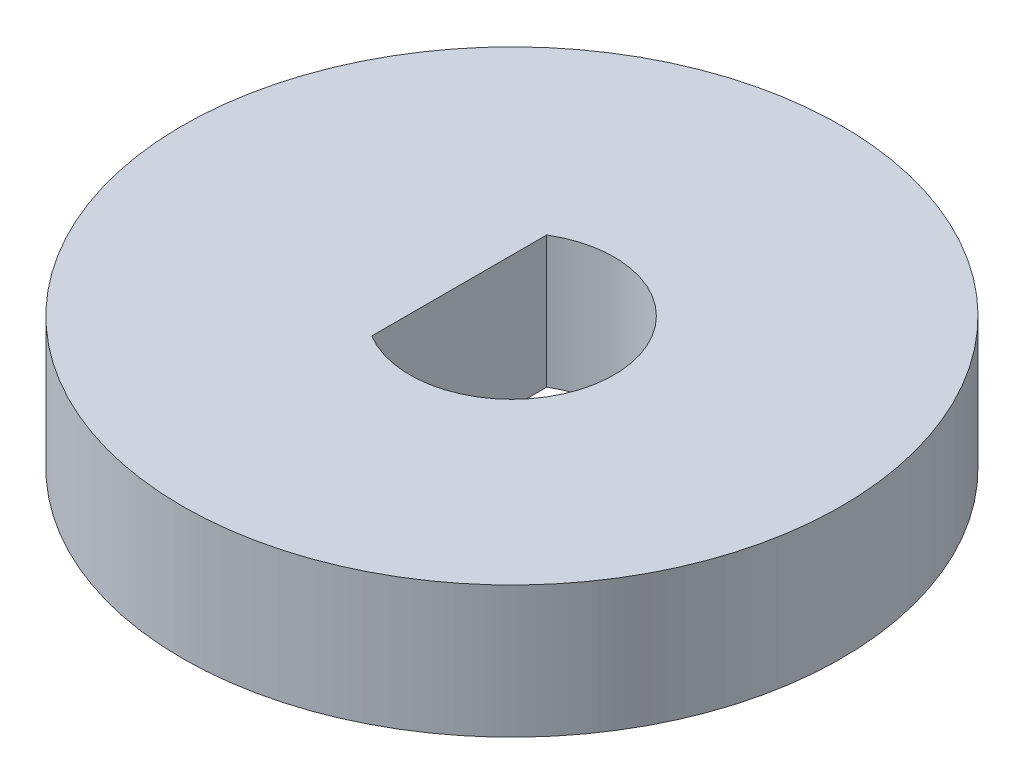
SolidWorks part; units mm, degrees
ref_plane "Plan de face" through (0, 0, 0) normal (0, 0, 1) x (1, 0, 0)
ref_plane "Plan de dessus" through (0, 0, 0) normal (0, 1, 0) x (1, 0, 0)
ref_plane "Plan de droite" through (0, 0, 0) normal (1, 0, 0) x (0, 0, -1)
sketch "Esquisse1" plane through (0, 0, 0) normal (0, 1, 0) x (1, 0, 0)
  line L6 (-1.6, -2.245) -> (-1.6, -2.6552)
  line L7 (-1.6, 2.6552) -> (-1.6, 2.245)
  line L8 (-1.6, 2.245) -> (-1.6, -2.245)
  line L9 (-1.6, -2.245) -> (-1.6, -2.6552)
  line L10 (-1.6, 2.6552) -> (-1.6, 2.245)
  line L11 (-1.6, 2.245) -> (-1.6, -2.245)
  circle A3 centre (0, 0) radius 10
  arc A6 (0, -3.1) -> (0, 3.1) centre (0, 0) ccw
  arc A7 (-1.6, -2.6552) -> (0, -3.1) centre (0, 0) ccw
  arc A8 (0, 3.1) -> (-1.6, 2.6552) centre (0, 0) ccw
  arc A9 (0, -3.1) -> (0, 3.1) centre (0, 0) ccw
  arc A10 (-1.6, -2.6552) -> (0, -3.1) centre (0, 0) ccw
  arc A11 (0, 3.1) -> (-1.6, 2.6552) centre (0, 0) ccw
  point P2 (-0.3086, -0.4749)
  point P3 (0, 0)
  dimension "D2" = 20
  dimension "D1" = 0.1
extrude "Boss.-Extru.1" add sketch "Esquisse1" against normal blind 4 from surface
